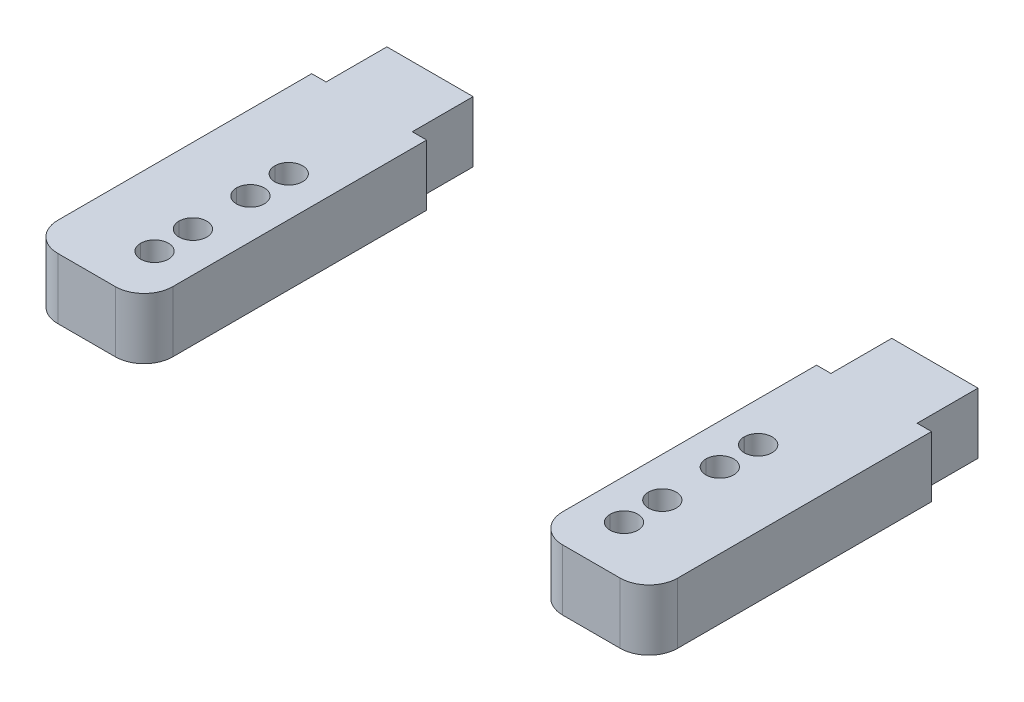
SolidWorks part; units mm, degrees
ref_plane "Front Plane" through (0, 0, 0) normal (0, 0, 1) x (1, 0, 0)
ref_plane "Top Plane" through (0, 0, 0) normal (0, 1, 0) x (1, 0, 0)
ref_plane "Right Plane" through (0, 0, 0) normal (1, 0, 0) x (0, 0, -1)
sketch "Sketch1" plane through (0, 0, 0) normal (0, 1, 0) x (1, 0, 0)
  line L0 (0, -27.5672) -> (0, 22.481) construction
  line L1 (0, 0) -> (52.8966, 0) construction
  line L2 (-32.35, -10.25) -> (-20.35, -10.25)
  line L3 (-20.35, -10.25) -> (-20.35, 19.25)
  line L4 (-20.35, 19.25) -> (-21.85, 19.25)
  line L5 (-32.35, 19.25) -> (-32.35, -10.25)
  line L6 (-24.5, -5.0005) -> (-24.5, -4.9995) construction
  line L7 (-25.95, -5.0005) -> (-25.95, -4.9995)
  line L8 (-23.05, -5.0005) -> (-23.05, -4.9995)
  line L9 (-24.5, 4.9995) -> (-24.5, 5.0005) construction
  line L10 (-25.95, 4.9995) -> (-25.95, 5.0005)
  line L11 (-23.05, 4.9995) -> (-23.05, 5.0005)
  line L12 (-30.85, 19.25) -> (-32.35, 19.25)
  line L13 (24.5, -5.0005) -> (24.5, -4.9995) construction
  line L14 (-30.85, 19.25) -> (-30.85, 25.6)
  line L15 (-30.85, 25.6) -> (-21.85, 25.6)
  line L16 (-21.85, 19.25) -> (-21.85, 25.6)
  line L17 (25.95, -5.0005) -> (25.95, -4.9995)
  line L18 (23.05, -5.0005) -> (23.05, -4.9995)
  line L19 (24.5, 4.9995) -> (24.5, 5.0005) construction
  line L20 (25.95, 4.9995) -> (25.95, 5.0005)
  line L21 (23.05, 4.9995) -> (23.05, 5.0005)
  line L22 (21.85, 19.25) -> (21.85, 25.6)
  line L23 (30.85, 25.6) -> (21.85, 25.6)
  line L24 (30.85, 19.25) -> (30.85, 25.6)
  line L25 (30.85, 19.25) -> (32.35, 19.25)
  line L26 (32.35, 19.25) -> (32.35, -10.25)
  line L27 (20.35, 19.25) -> (21.85, 19.25)
  line L28 (20.35, -10.25) -> (20.35, 19.25)
  line L29 (32.35, -10.25) -> (20.35, -10.25)
  line L30 (-32.35, 10.25) -> (-20.35, 10.25) construction
  line L31 (-24.5, -1.0005) -> (-24.5, -0.9995) construction
  line L32 (-25.95, -1.0005) -> (-25.95, -0.9995)
  line L33 (-23.05, -1.0005) -> (-23.05, -0.9995)
  line L34 (-24.5, 8.9995) -> (-24.5, 9.0005) construction
  line L35 (-25.95, 8.9995) -> (-25.95, 9.0005)
  line L36 (-23.05, 8.9995) -> (-23.05, 9.0005)
  line L37 (24.5, 8.9995) -> (24.5, 9.0005) construction
  line L38 (25.95, 8.9995) -> (25.95, 9.0005)
  line L39 (23.05, 8.9995) -> (23.05, 9.0005)
  line L40 (24.5, -1.0005) -> (24.5, -0.9995) construction
  line L41 (25.95, -1.0005) -> (25.95, -0.9995)
  line L42 (23.05, -1.0005) -> (23.05, -0.9995)
  arc A0 (-25.95, 4.9995) -> (-23.05, 4.9995) centre (-24.5, 4.9995) ccw
  arc A1 (-23.05, 5.0005) -> (-25.95, 5.0005) centre (-24.5, 5.0005) ccw
  arc A2 (-25.95, -5.0005) -> (-23.05, -5.0005) centre (-24.5, -5.0005) ccw
  arc A3 (-23.05, -4.9995) -> (-25.95, -4.9995) centre (-24.5, -4.9995) ccw
  arc A4 (25.95, -5.0005) -> (23.05, -5.0005) centre (24.5, -5.0005) cw
  arc A5 (23.05, -4.9995) -> (25.95, -4.9995) centre (24.5, -4.9995) cw
  arc A6 (25.95, 4.9995) -> (23.05, 4.9995) centre (24.5, 4.9995) cw
  arc A7 (23.05, 5.0005) -> (25.95, 5.0005) centre (24.5, 5.0005) cw
  arc A8 (-25.95, -1.0005) -> (-23.05, -1.0005) centre (-24.5, -1.0005) ccw
  arc A9 (-23.05, -0.9995) -> (-25.95, -0.9995) centre (-24.5, -0.9995) ccw
  arc A10 (-25.95, 8.9995) -> (-23.05, 8.9995) centre (-24.5, 8.9995) ccw
  arc A11 (-23.05, 9.0005) -> (-25.95, 9.0005) centre (-24.5, 9.0005) ccw
  arc A12 (25.95, 8.9995) -> (23.05, 8.9995) centre (24.5, 8.9995) cw
  arc A13 (23.05, 9.0005) -> (25.95, 9.0005) centre (24.5, 9.0005) cw
  arc A14 (25.95, -1.0005) -> (23.05, -1.0005) centre (24.5, -1.0005) cw
  arc A15 (23.05, -0.9995) -> (25.95, -0.9995) centre (24.5, -0.9995) cw
  point P11 (-24.5, 5)
  point P15 (-24.5, -5)
  point P29 (24.5, -5)
  point P36 (24.5, 5)
  point P55 (-24.5, 9)
  point P59 (-24.5, -1)
  point P67 (24.5, 9)
  point P74 (24.5, -1)
  dimension "D7" = 1.45
  dimension "D8" = 10
  dimension "D6" = 5
  dimension "D10" = 6.35
  dimension "D1" = 29.5
  dimension "D2" = 12
  dimension "D3" = 20.35
  dimension "D4" = 10.25
  dimension "D5" = 24.5
  dimension "D9" = 0.001
  dimension "D11" = 1.5
  dimension "D12" = 1.5
  dimension "D13" = 20.5
  dimension "D14" = 2
extrude "Boss-Extrude1" add sketch "Sketch1" along normal blind 6.35
fillet "Fillet1" radius 3 2 edges at (-20.35, 3.175, 10.25) (-32.35, 3.175, 10.25)
fillet "Fillet2" radius 3 2 edges at (32.35, 3.175, 10.25) (20.35, 3.175, 10.25)
